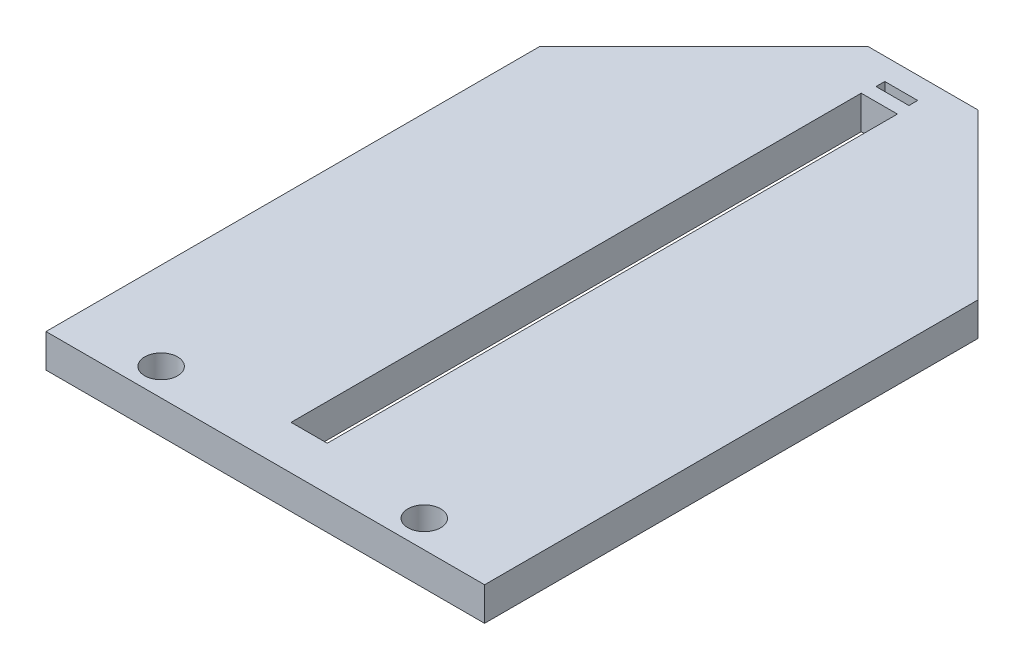
SolidWorks part; units mm, degrees
ref_plane "Front Plane" through (0, 0, 0) normal (0, 0, 1) x (1, 0, 0)
ref_plane "Top Plane" through (0, 0, 0) normal (0, 1, 0) x (1, 0, 0)
ref_plane "Right Plane" through (0, 0, 0) normal (1, 0, 0) x (0, 0, -1)
sketch "Sketch1" plane through (0, 0, 0) normal (0, 1, 0) x (1, 0, 0)
  line L1 (0, 0) -> (40, 0)
  line L2 (0, 0) -> (0, 60)
  line L3 (0, 60) -> (40, 60)
  line L4 (40, 0) -> (40, 60)
  dimension "D1" = 40
  dimension "D2" = 60
extrude "Boss-Extrude1" add sketch "Sketch1" along normal blind 3.05
sketch "Sketch4" plane through (0, 3.05, 0) normal (0, 1, 0) x (1, 0, 0)
  line L0 (20, 60) -> (20, 58)
  line L1 (0, 60) -> (40, 60) construction
  line L3 (21.5, 58) -> (18.5, 58)
  line L4 (18.5, 58) -> (18.5, 57.2)
  line L5 (18.5, 57.2) -> (21.5, 57.2)
  line L6 (21.5, 57.2) -> (21.5, 58)
  line L7 (20, 57.2) -> (20, 56)
  line L9 (21.65, 56) -> (18.35, 56)
  line L10 (18.35, 56) -> (18.35, 4)
  line L11 (18.35, 4) -> (21.65, 4)
  line L12 (21.65, 4) -> (21.65, 56)
  point P10 (20, 58)
  point P22 (20, 56)
  dimension "D1" = 2
  dimension "D2" = 0.8
  dimension "D3" = 1.2
  dimension "D4" = 3
  dimension "D5" = 52
  dimension "D6" = 3.3
extrude "Cut-Extrude1" cut sketch "Sketch4" against normal blind 10 contours L11 L12 L9 L10 | L5 L6 L3 L4
sketch "Sketch5" plane through (0, 3.05, 0) normal (0, 1, 0) x (1, 0, 0)
  line L0 (0, 60) -> (0, 20)
  line L1 (0, 0) -> (0, 60) construction
  line L2 (0, 60) -> (15, 60)
  line L3 (0, 60) -> (40, 60) construction
  line L5 (40, 60) -> (25, 60)
  line L6 (40, 60) -> (40, 20)
  line L7 (40, 0) -> (40, 60) construction
  line L9 (15, 60) -> (15, 20)
  line L10 (15, 20) -> (0, 20)
  line L11 (25, 60) -> (25, 20)
  line L12 (25, 20) -> (40, 20)
  circle A0 centre (7.5, 27.5) radius 7.5
  circle A1 centre (32.5, 27.5) radius 7.5
  line M14 (40, 0) -> (40, 60)
  line M15 (40, 60) -> (0, 60)
  line M16 (0, 60) -> (0, 0)
  dimension "D1" = 40
  dimension "D2" = 15
  dimension "D3" = 40
  dimension "D4" = 15
extrude "Cut-Extrude2" [suppressed] cut sketch "Sketch5" against normal blind 10 contours A0 L9 M15 M16 | A0 | A0 L0 L10 | A1 L6 L11 M15 | A1 | A1 L12 M14
sketch "Sketch6" plane through (0, 3.05, 0) normal (0, 1, 0) x (1, 0, 0)
  line L0 (0, 60) -> (0, 45)
  line L1 (0, 0) -> (0, 60) construction
  line L2 (0, 60) -> (15, 60)
  line L3 (0, 60) -> (40, 60) construction
  line L4 (40, 60) -> (40, 45)
  line L5 (40, 0) -> (40, 60) construction
  line L6 (40, 60) -> (25, 60)
  line L7 (15, 60) -> (0, 45)
  line L8 (25, 60) -> (40, 45)
  dimension "D1" = 15
  dimension "D2" = 15
  dimension "D3" = 15
  dimension "D4" = 15
extrude "Cut-Extrude3" cut sketch "Sketch6" against normal blind 10
sketch "Sketch7" plane through (0, 3.05, 0) normal (0, 1, 0) x (1, 0, 0)
  line L0 (0, 0) -> (8, 0)
  line L1 (0, 0) -> (40, 0) construction
  line L2 (8, 0) -> (8, 2.5)
  line L3 (8, 2.5) -> (32, 2.5)
  circle A0 centre (8, 2.5) radius 1.5
  circle A1 centre (32, 2.5) radius 1.5
  dimension "D3" = 3
  dimension "D5" = 3
  dimension "D1" = 8
  dimension "D2" = 2.5
  dimension "D4" = 24
extrude "Cut-Extrude4" cut sketch "Sketch7" against normal blind 10
